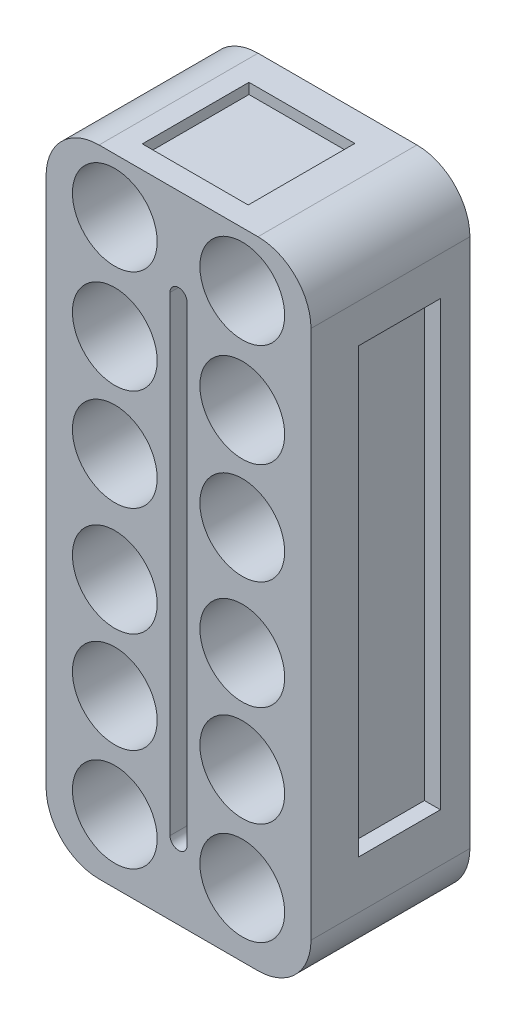
SolidWorks part; units mm, degrees
material "Oak"
ref_plane "Front" through (0, 0, 0) normal (0, 0, 1) x (1, 0, 0)
ref_plane "Top" through (0, 0, 0) normal (0, 1, 0) x (1, 0, 0)
ref_plane "Right" through (0, 0, 0) normal (1, 0, 0) x (0, 0, -1)
sketch "Sketch1" plane through (0, 0, 0) normal (0, 0, 1) x (1, 0, 0)
  line L1 (-15, 120) -> (15, 120)
  line L2 (-25, 110) -> (-25, 10)
  line L3 (-15, 0) -> (15, 0)
  line L4 (25, 110) -> (25, 10)
  line L5 (-25, 120) -> (25, 0) construction
  line L6 (-25, 0) -> (25, 120) construction
  arc A0 (15, 0) -> (25, 10) centre (15, 10) ccw
  arc A1 (-25, 10) -> (-15, 0) centre (-15, 10) ccw
  arc A2 (15, 120) -> (25, 110) centre (15, 110) cw
  arc A3 (-15, 120) -> (-25, 110) centre (-15, 110) ccw
  point P4 (0, 60)
  dimension "D1" = 10
extrude "Boss-Extrude4" add sketch "Sketch1" along normal blind 15
sketch "Sketch2" plane through (0, 0, 15) normal (0, 0, 1) x (1, 0, 0)
  line L0 (0, 123.7713) -> (0, -3.3334) construction
  arc M1 (15, 0) -> (25, 10) centre (15, 10) ccw
  line M2 (25, 10) -> (25, 110)
  arc M3 (25, 110) -> (15, 120) centre (15, 110) ccw
  line M4 (15, 120) -> (-15, 120)
  arc M5 (-15, 120) -> (-25, 110) centre (-15, 110) ccw
  line M6 (-25, 110) -> (-25, 10)
  arc M7 (-25, 10) -> (-15, 0) centre (-15, 10) ccw
  line M8 (-15, 0) -> (15, 0)
extrude "Boss-Extrude5" add sketch "Sketch2" along normal blind 15 contours L0 M4 M8 M1 M2 M3 | L0 M4 M5 M6 M7 M8
sketch "Sketch3" plane through (0, 0, 30) normal (0, 0, 1) x (1, 0, 0)
  line L0 (0, 1.6403) -> (0, 120) construction
  line L1 (15, 120) -> (-15, 120) construction
  circle A0 centre (-12.0332, 109.6562) radius 8
  circle A1 centre (-12.0332, 90.1766) radius 8
  circle A2 centre (-12.0332, 70.9978) radius 8
  circle A3 centre (-12.0332, 50.4579) radius 8
  circle A4 centre (-12.0332, 31.4224) radius 8
  circle A5 centre (-12.0332, 12.0502) radius 8
  circle A6 centre (12.0332, 12.0502) radius 8
  circle A7 centre (12.0332, 31.4224) radius 8
  circle A8 centre (12.0332, 50.4579) radius 8
  circle A9 centre (12.0332, 70.9978) radius 8
  circle A10 centre (12.0332, 90.1766) radius 8
  circle A11 centre (12.0332, 109.6562) radius 8
extrude "Cut-Extrude2" cut sketch "Sketch3" against normal blind 15
sketch "Sketch4" plane through (0, 0, 30) normal (0, 0, 1) x (1, 0, 0)
  line L0 (0, 13.7909) -> (0, 102.59) construction
  line L1 (-1.6123, 13.7909) -> (-1.6123, 102.59)
  line L2 (1.6123, 13.7909) -> (1.6123, 102.59)
  arc A0 (-1.6123, 13.7909) -> (1.6123, 13.7909) centre (0, 13.7909) ccw
  arc A1 (1.6123, 102.59) -> (-1.6123, 102.59) centre (0, 102.59) ccw
  point P3 (0, 58.1904)
extrude "Cut-Extrude3" cut sketch "Sketch4" against normal blind 5
sketch "Sketch5" plane through (0, 0, 0) normal (0, -1, 0) x (-1, 0, 0)
  line L1 (-9.8986, -23.6191) -> (13.5227, -23.6191)
  line L2 (-9.8986, -23.6191) -> (-9.8986, -5.3319)
  line L3 (-9.8986, -5.3319) -> (13.5227, -5.3319)
  line L4 (13.5227, -23.6191) -> (13.5227, -5.3319)
  line L5 (-9.8986, -23.6191) -> (13.5227, -5.3319) construction
  line L6 (-9.8986, -5.3319) -> (13.5227, -23.6191) construction
  point P4 (1.812, -14.4755)
extrude "Cut-Extrude5" cut sketch "Sketch5" against normal blind 3
sketch "Sketch6" plane through (0, 120, 0) normal (0, 1, 0) x (1, 0, 0)
  line L1 (8.8889, -5.6082) -> (-11.0956, -5.6082)
  line L2 (8.8889, -5.6082) -> (8.8889, -25.7394)
  line L3 (8.8889, -25.7394) -> (-11.0956, -25.7394)
  line L4 (-11.0956, -5.6082) -> (-11.0956, -25.7394)
  line L5 (8.8889, -5.6082) -> (-11.0956, -25.7394) construction
  line L6 (8.8889, -25.7394) -> (-11.0956, -5.6082) construction
  point P4 (-1.1033, -15.6738)
extrude "Cut-Extrude7" cut sketch "Sketch6" against normal blind 2
sketch "Sketch7" plane through (-25, 0, 0) normal (-1, 0, 0) x (0, 0, 1)
  line L1 (23.2369, 98.9667) -> (6.3237, 98.9667)
  line L2 (23.2369, 98.9667) -> (23.2369, 18.6979)
  line L3 (23.2369, 18.6979) -> (6.3237, 18.6979)
  line L4 (6.3237, 98.9667) -> (6.3237, 18.6979)
  line L5 (23.2369, 98.9667) -> (6.3237, 18.6979) construction
  line L6 (23.2369, 18.6979) -> (6.3237, 98.9667) construction
  point P4 (14.7803, 58.8323)
extrude "Cut-Extrude8" cut sketch "Sketch7" against normal blind 3
sketch "Sketch8" plane through (25, 0, 0) normal (1, 0, 0) x (0, 0, -1)
  line L1 (-21.0572, 19.1137) -> (-5.5761, 19.1137)
  line L2 (-21.0572, 19.1137) -> (-21.0572, 102.6767)
  line L3 (-21.0572, 102.6767) -> (-5.5761, 102.6767)
  line L4 (-5.5761, 19.1137) -> (-5.5761, 102.6767)
  line L5 (-21.0572, 19.1137) -> (-5.5761, 102.6767) construction
  line L6 (-21.0572, 102.6767) -> (-5.5761, 19.1137) construction
  point P4 (-13.3166, 60.8952)
extrude "Cut-Extrude9" cut sketch "Sketch8" against normal blind 3
